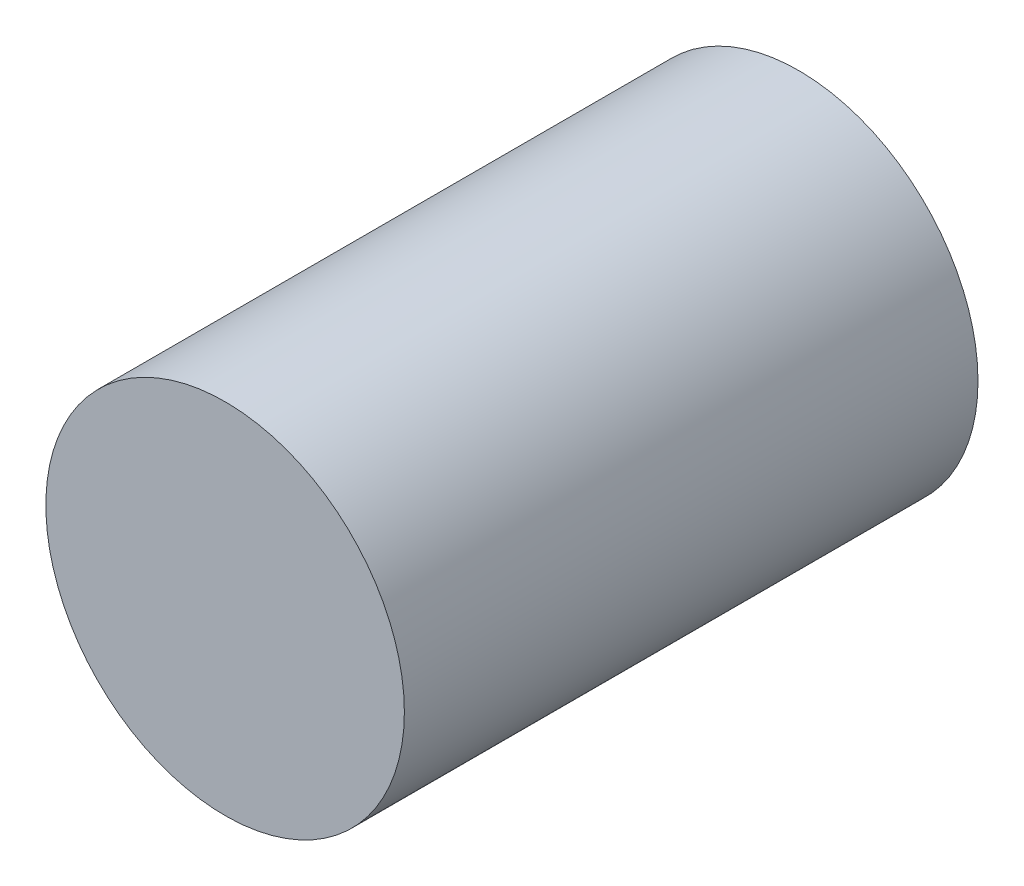
SolidWorks part; units mm, degrees
ref_plane "Plan de face" through (0, 0, 0) normal (0, 0, 1) x (1, 0, 0)
ref_plane "Plan de dessus" through (0, 0, 0) normal (0, 1, 0) x (1, 0, 0)
ref_plane "Plan de droite" through (0, 0, 0) normal (1, 0, 0) x (0, 0, -1)
sketch "Esquisse1" plane through (0, 0, 0) normal (0, 0, 1) x (1, 0, 0)
  circle A0 centre (0, 0) radius 2.5
  dimension "D1" = 5
extrude "Boss.-Extru.1" add sketch "Esquisse1" along normal blind 8
